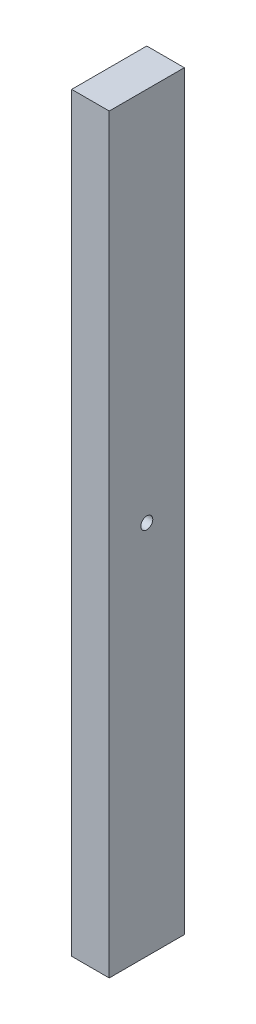
SolidWorks part; units mm, degrees
ref_plane "Спереди" through (0, 0, 0) normal (0, 0, 1) x (1, 0, 0)
ref_plane "Сверху" through (0, 0, 0) normal (0, 1, 0) x (1, 0, 0)
ref_plane "Справа" through (0, 0, 0) normal (1, 0, 0) x (0, 0, -1)
other "Configuration Table"
sketch "Эскиз1" plane through (0, 0, 0) normal (0, 1, 0) x (1, 0, 0)
  line L1 (12.5, 25) -> (-12.5, 25)
  line L2 (12.5, 25) -> (12.5, -25)
  line L3 (12.5, -25) -> (-12.5, -25)
  line L4 (-12.5, 25) -> (-12.5, -25)
  line L5 (12.5, 25) -> (-12.5, -25) construction
  line L6 (12.5, -25) -> (-12.5, 25) construction
  point P0 (0, 0)
extrude "Бобышка-Вытянуть1" add sketch "Эскиз1" along normal blind 550
sketch "Эскиз2" plane through (0, 550, 0) normal (0, 1, 0) x (1, 0, 0)
  circle A0 centre (0, 0) radius 4
extrude "Вырез-Вытянуть1" cut sketch "Эскиз2" against normal blind 10
sketch "Эскиз3" plane through (0, 0, 0) normal (0, -1, 0) x (1, 0, 0)
  circle A0 centre (0, 0) radius 4
extrude "Вырез-Вытянуть2" cut sketch "Эскиз3" against normal blind 10
sketch "Эскиз4" plane through (0, 550, 0) normal (0, 1, 0) x (1, 0, 0)
  line L4 (-12.5, 25) -> (-12.5, -25)
  line L5 (-12.5, -25) -> (12.5, -25)
  line L6 (12.5, -25) -> (12.5, 25)
  line L7 (12.5, 25) -> (-12.5, 25)
  line L8 (-12.5, 25) -> (-12.5, -25)
  line L9 (-12.5, -25) -> (12.5, -25)
  line L10 (12.5, -25) -> (12.5, 25)
  line L11 (12.5, 25) -> (-12.5, 25)
  dimension "D1" = 0
extrude "Вырез-Вытянуть3" cut sketch "Эскиз4" against normal blind 50
sketch "Эскиз5" plane through (12.5, 0, 0) normal (1, 0, 0) x (0, 0, -1)
  line L0 (0, 500) -> (0, 0) construction
  line L1 (-25, 500) -> (25, 500) construction
  circle A0 centre (0, 250) radius 4
extrude "Вырез-Вытянуть4" cut sketch "Эскиз5" against normal blind 51
